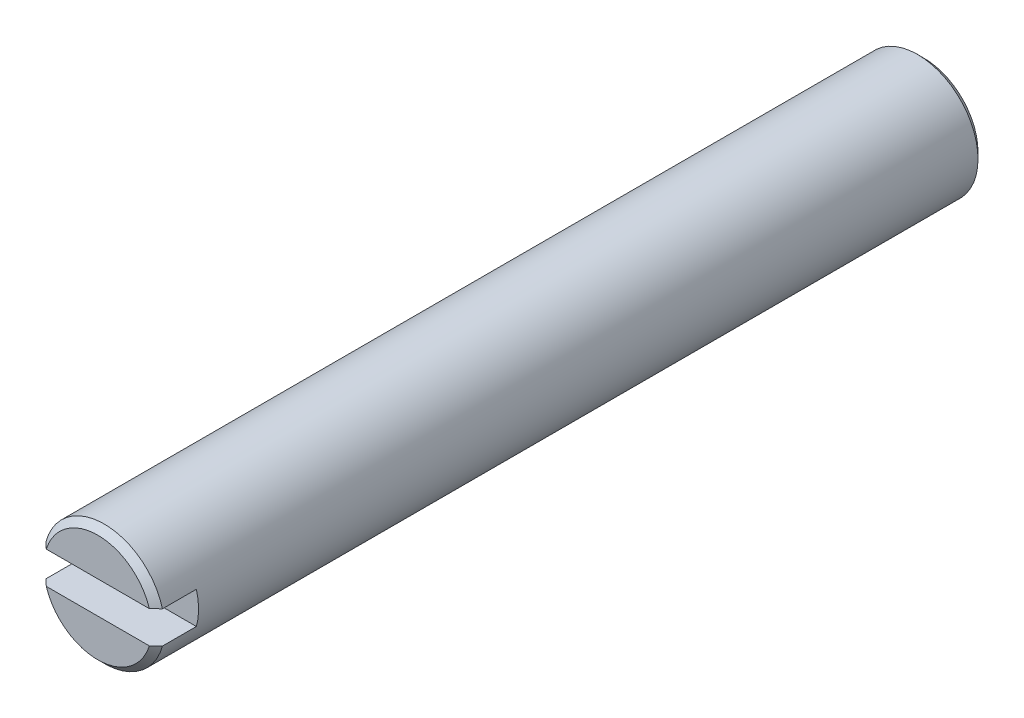
SolidWorks part; units mm, degrees
ref_plane "Front Plane" through (0, 0, 0) normal (0, 0, 1) x (1, 0, 0)
ref_plane "Top Plane" through (0, 0, 0) normal (0, 1, 0) x (1, 0, 0)
ref_plane "Right Plane" through (0, 0, 0) normal (1, 0, 0) x (0, 0, -1)
sketch "Sketch1" plane through (0, 0, 0) normal (0, 0, 1) x (1, 0, 0)
  circle A0 centre (0, 0) radius 0.1875
  dimension "D1" = 0.375
extrude "Boss-Extrude1" add sketch "Sketch1" along normal blind 2.563
ref_plane "Plane1" through (0, 0, 2.563) normal (0, 0, 1) x (1, 0, 0)
sketch "Sketch2" plane through (0, 0, 2.563) normal (0, 0, 1) x (1, 0, 0)
  line L1 (-0.1807, 0.05) -> (0.1807, 0.05)
  line L2 (-0.1807, -0.05) -> (0.1807, -0.05)
  circle A0 centre (0, 0) radius 0.1875 construction
  circle A1 centre (0, 0) radius 0.1875
  arc A2 (-0.1807, 0.05) -> (-0.1807, -0.05) centre (0, 0) ccw
  arc A3 (0.1807, 0.05) -> (0.1807, -0.05) centre (0, 0) ccw
  point P6 (0, 0)
  point P9 (0, 0.05)
  point P12 (0, -0.05)
extrude "Cut-Extrude1" cut sketch "Sketch2" against normal blind 0.125 contours L1 A1 L2
chamfer "Chamfer1" distance 0.02 angle 45 1 edges at (0, 0.1875, 2.563)
chamfer "Chamfer2" distance 0.02 angle 45 1 edges at (0, -0.1875, 2.563)
chamfer "Chamfer3" distance 0.02 angle 45 1 edges at (0.1875, 0, 0)
